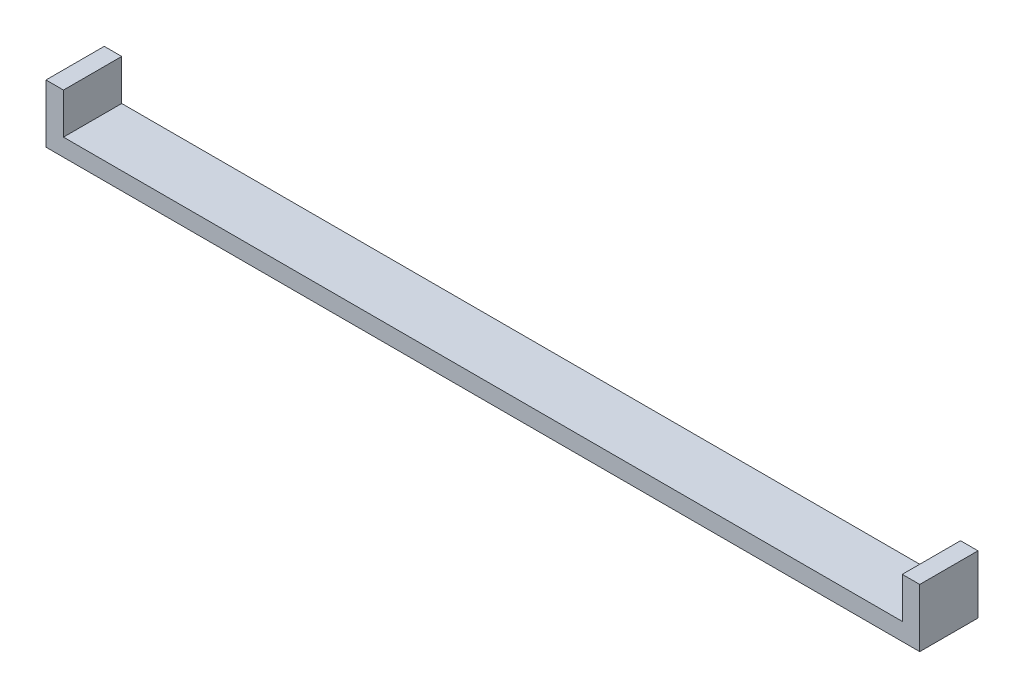
SolidWorks part; units mm, degrees
ref_plane "Front Plane" through (0, 0, 0) normal (0, 0, 1) x (1, 0, 0)
ref_plane "Top Plane" through (0, 0, 0) normal (0, 1, 0) x (1, 0, 0)
ref_plane "Right Plane" through (0, 0, 0) normal (1, 0, 0) x (0, 0, -1)
sketch "Sketch1" plane through (0, 0, 0) normal (0, 0, 1) x (1, 0, 0)
  line L0 (-74.3534, -37.931) -> (75.6466, -37.931)
  line L1 (75.6466, -37.931) -> (75.6466, -27.931)
  line L2 (75.6466, -27.931) -> (72.6466, -27.931)
  line L3 (72.6466, -27.931) -> (72.6466, -34.931)
  line L4 (72.6466, -34.931) -> (-71.3534, -34.931)
  line L5 (-71.3534, -34.931) -> (-71.3534, -27.931)
  line L6 (-71.3534, -27.931) -> (-74.3534, -27.931)
  line L7 (-74.3534, -27.931) -> (-74.3534, -37.931)
  dimension "D1" = 150
  dimension "D2" = 3
  dimension "D3" = 3
  dimension "D4" = 3
  dimension "D5" = 10
  dimension "D6" = 10
  dimension "D7" = 3
  dimension "D8" = 7
  dimension "D9" = 7
extrude "Boss-Extrude1" add sketch "Sketch1" along normal blind 10
